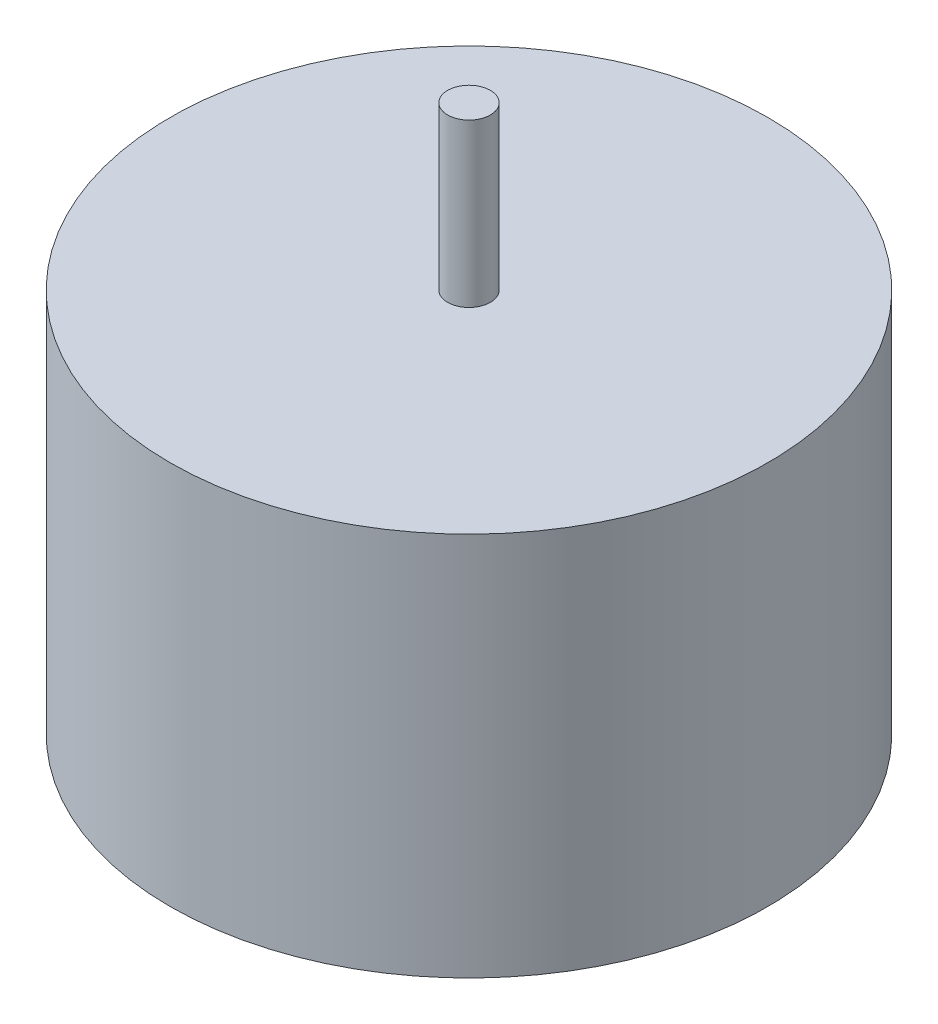
SolidWorks part; units mm, degrees
ref_plane "前视基准面" through (0, 0, 0) normal (0, 0, 1) x (1, 0, 0)
ref_plane "上视基准面" through (0, 0, 0) normal (0, 1, 0) x (1, 0, 0)
ref_plane "右视基准面" through (0, 0, 0) normal (1, 0, 0) x (0, 0, -1)
sketch "草图1" plane through (0, 0, 0) normal (0, 1, 0) x (1, 0, 0)
  circle A0 centre (0, 0) radius 7
extrude "凸台-拉伸1" add sketch "草图1" along normal blind 9
sketch "草图2" plane through (0, 0, 0) normal (0, -1, 0) x (1, 0, 0)
  circle A0 centre (0, 4.5) radius 1
  circle A1 centre (0, -4.5) radius 1
  circle A2 centre (4.5, 0) radius 1
  circle A3 centre (-4.5, 0) radius 1
  dimension "D1" = 2
extrude "切除-拉伸2" cut sketch "草图2" against normal blind 2.5
sketch "草图3" plane through (0, 9, 0) normal (0, 1, 0) x (1, 0, 0)
  circle A0 centre (0, 0) radius 0.5
extrude "凸台-拉伸2" add sketch "草图3" along normal blind 3.8
